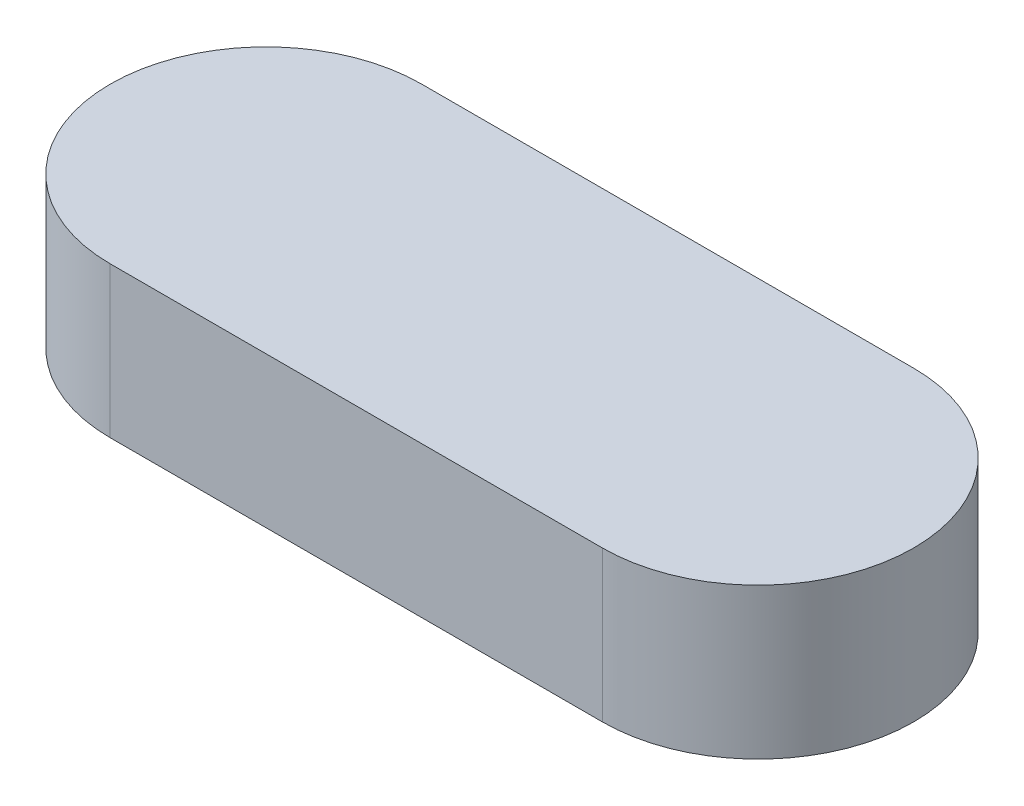
SolidWorks part; units mm, degrees
ref_plane "Front Plane" through (0, 0, 0) normal (0, 0, 1) x (1, 0, 0)
ref_plane "Top Plane" through (0, 0, 0) normal (0, 1, 0) x (1, 0, 0)
ref_plane "Right Plane" through (0, 0, 0) normal (1, 0, 0) x (0, 0, -1)
sketch "Sketch1" plane through (0, 0, 0) normal (0, 1, 0) x (1, 0, 0)
  line L0 (-12.25, 0) -> (12.25, 0) construction
  line L1 (-12.25, 7.75) -> (12.25, 7.75)
  line L2 (-12.25, -7.75) -> (12.25, -7.75)
  arc A0 (-12.25, 7.75) -> (-12.25, -7.75) centre (-12.25, 0) ccw
  arc A1 (12.25, -7.75) -> (12.25, 7.75) centre (12.25, 0) ccw
  point P3 (0, 0)
  dimension "D2" = 7.75
  dimension "D3" = 12.25
  dimension "D1" = 24.5
extrude "Boss-Extrude1" add sketch "Sketch1" along normal blind 7.5
